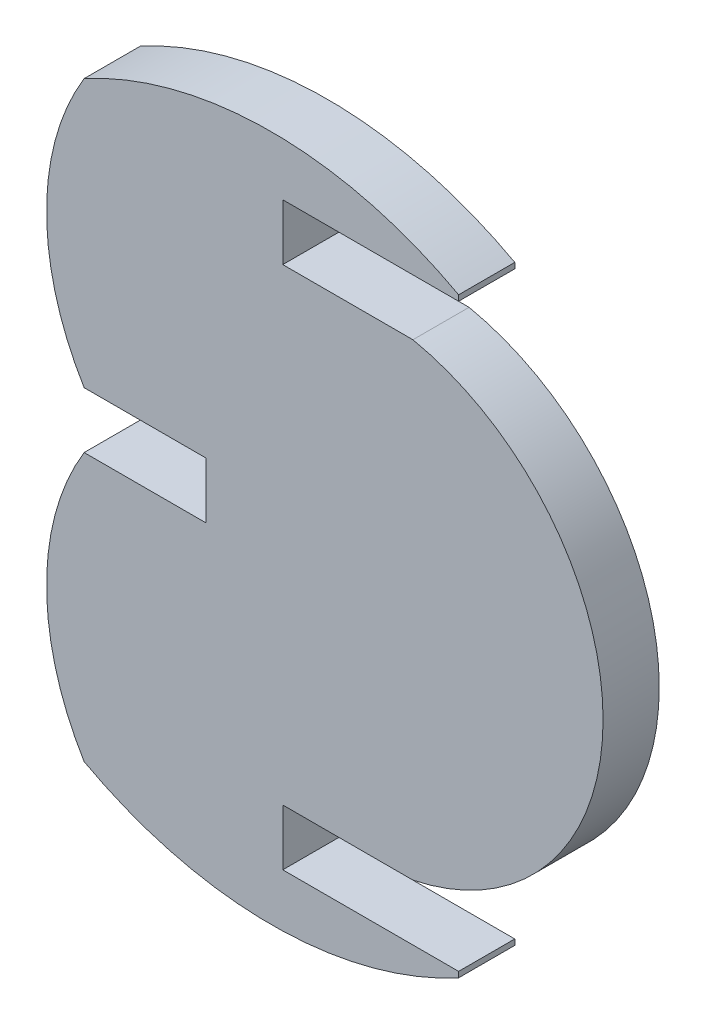
SolidWorks part; units mm, degrees
ref_plane "Front" through (0, 0, 0) normal (0, 0, 1) x (1, 0, 0)
ref_plane "Top" through (0, 0, 0) normal (0, 1, 0) x (1, 0, 0)
ref_plane "Right" through (0, 0, 0) normal (1, 0, 0) x (0, 0, -1)
sketch "Sketch1" plane through (0, 0, 0) normal (0, 0, 1) x (1, 0, 0)
  line L4 (-1361.6767, 33.6928) -> (-1355.1571, 33.6928)
  line L5 (-1351.0658, 22.6928) -> (-1344.1134, 22.6928)
  line L6 (-1351.0658, 19.6928) -> (-1351.0658, 22.6928)
  line L8 (-1355.1571, 33.6928) -> (-1355.1571, 36.6928)
  line L9 (-1351.0658, 19.6928) -> (-1341.6721, 19.6928)
  line L10 (-1341.6721, 19.3921) -> (-1341.6721, 19.6928)
  line L11 (-1341.6721, 50.9936) -> (-1341.6721, 50.6928)
  line L12 (-1340.5335, 35.1928) -> (-1355.1571, 35.1928) construction
  line L13 (-1351.0658, 50.6928) -> (-1341.6721, 50.6928)
  line L14 (-1351.0658, 50.6928) -> (-1351.0658, 47.6928)
  line L15 (-1351.0658, 47.6928) -> (-1344.1134, 47.6928)
  line L16 (-1361.6767, 36.6928) -> (-1355.1571, 36.6928)
  arc A0 (-1361.6767, 50.9936) -> (-1361.6767, 36.6928) centre (-1349.9372, 43.8432) ccw
  arc A1 (-1361.6767, 50.9936) -> (-1341.6721, 50.9936) centre (-1351.6744, 32.5979) cw
  arc A2 (-1344.1134, 47.6928) -> (-1344.1134, 22.6928) centre (-1346.7242, 35.1928) cw
  arc A3 (-1361.6767, 19.3921) -> (-1341.6721, 19.3921) centre (-1351.6744, 37.7878) ccw
  arc A5 (-1361.6767, 19.3921) -> (-1361.6767, 33.6928) centre (-1349.9372, 26.5425) cw
  dimension "D3" = 3
  dimension "D5" = 6.9523
  dimension "D6" = 3
  dimension "D7" = 25
  dimension "D8" = 31
extrude "Base-Extrude" add sketch "Sketch1" along normal blind 3
